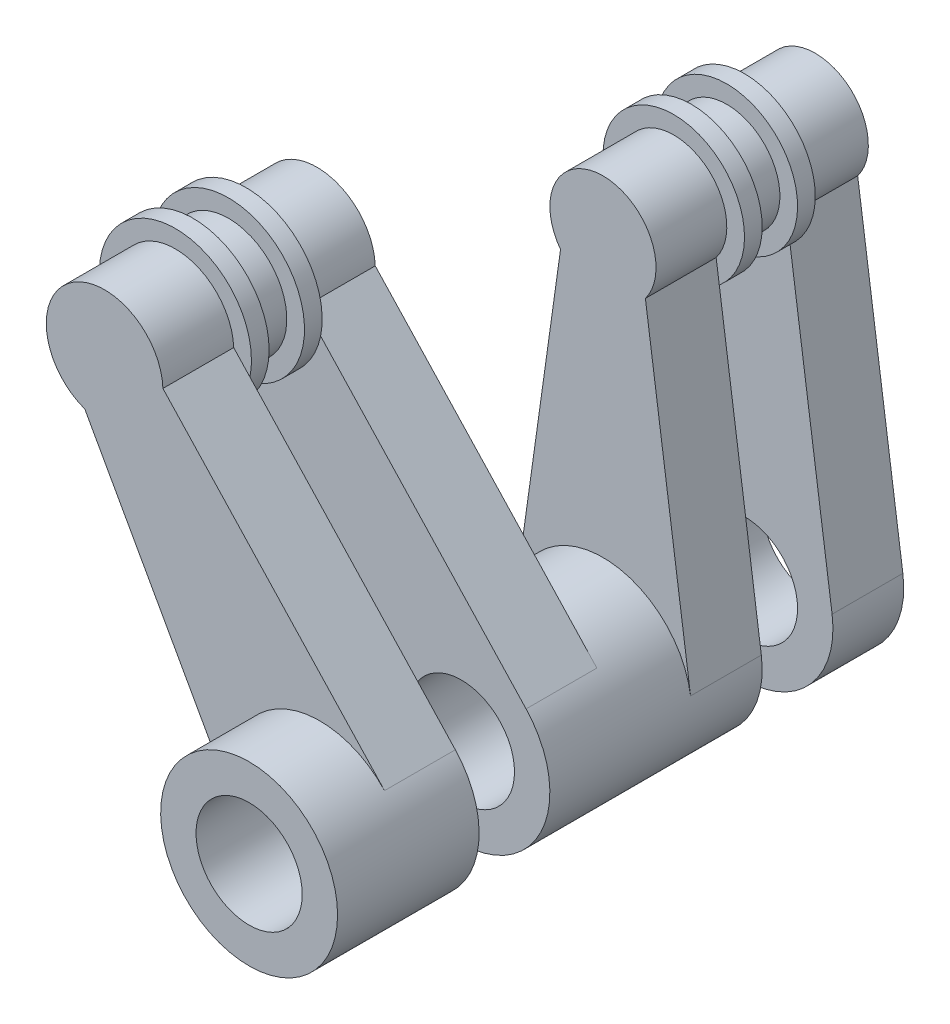
SolidWorks part; units mm, degrees
material "Ferro fundido maleável"
ref_plane "Plano frontal" through (0, 0, 0) normal (0, 0, 1) x (1, 0, 0)
ref_plane "Plano superior" through (0, 0, 0) normal (0, 1, 0) x (1, 0, 0)
ref_plane "Plano direito" through (0, 0, 0) normal (1, 0, 0) x (0, 0, -1)
sketch "Esboço1" plane through (0, 0, 0) normal (0, 0, 1) x (1, 0, 0)
  line L0 (-1.1988, 9.4384) -> (-2.4757, 0.3477)
  line L1 (1.1989, 9.4385) -> (2.4757, 0.3477)
  arc A0 (-2.4757, 0.3477) -> (2.4757, 0.3477) centre (0, 0) ccw
  arc A1 (1.1989, 9.4385) -> (-1.1988, 9.4384) centre (0, 10.34) ccw
  circle A2 centre (0, 0) radius 1.5
  dimension "D1" = 5
  dimension "D2" = 3
  dimension "D4" = 9.1799
  dimension "D3" = 10.34
  dimension "D5" = 9.18
extrude "Ressalto-extrusão1" add sketch "Esboço1" along normal blind 2
sketch "Esboço2" plane through (0, 0, 2) normal (0, 0, 1) x (1, 0, 0)
  circle A0 centre (0, 10.34) radius 1.5
extrude "Ressalto-extrusão2" add sketch "Esboço2" along normal blind 1
mirror "Espelhar1" about plane through (0, 10.34, 3) normal (0, 0, 1) of bodies 128
sketch "Esboço4" plane through (0, 0, 6) normal (0, 0, 1) x (1, 0, 0)
  circle A0 centre (0, 0) radius 2.5
  circle A1 centre (0, 0) radius 1.5
extrude "Ressalto-extrusão3" add sketch "Esboço4" along normal blind 2
sketch "Esboço5" plane through (0, 0, 8) normal (0, 0, 1) x (1, 0, 0)
  line L4 (0, 0) -> (-6.0836, 8.361) construction
  line L5 (0, 0) -> (0, 10.34) construction
  line L6 (-6.6438, 6.8104) -> (-2.1854, -1.2142)
  line L7 (-4.4359, 8.4169) -> (1.8277, 1.7058)
  arc A5 (-2.1854, -1.2142) -> (1.8277, 1.7058) centre (0, 0) ccw
  arc A7 (-4.4359, 8.4169) -> (-6.6438, 6.8104) centre (-6.0836, 8.361) ccw
  circle A9 centre (0, 0) radius 1.5
  dimension "D1" = 10.34
  dimension "D2" = 36.04
  dimension "D3" = 10.34
  dimension "D4" = 5
  dimension "D5" = 3
  dimension "D6" = 3.2972
  dimension "D7" = 9.18
  dimension "D8" = 9.18
extrude "Ressalto-extrusão4" add sketch "Esboço5" along normal blind 2
sketch "Esboço6" plane through (0, 0, 10) normal (0, 0, 1) x (1, 0, 0)
  circle A0 centre (-6.0836, 8.361) radius 1.6486
extrude "Ressalto-extrusão5" add sketch "Esboço6" along normal blind 1
mirror "Espelhar3" about plane through (-6.0836, 8.361, 11) normal (0, 0, 1) of bodies 132
sketch "Esboço7" plane through (0, 0, 22) normal (0, 0, 1) x (1, 0, 0)
  line L1 (-6.2358, 12.3393) -> (5.7031, 12.3393)
  line L2 (-6.2358, 12.3393) -> (-6.2358, -3.3992)
  line L3 (-6.2358, -3.3992) -> (5.7031, -3.3992)
  line L4 (5.7031, 12.3393) -> (5.7031, -3.3992)
extrude "Corte-extrusão1" cut sketch "Esboço7" against normal up to surface (6 mm away) up to face at (0, 6.0315, 16)
sketch "Esboço8" plane through (0, 0, 14) normal (0, 0, 1) x (1, 0, 0)
  circle A2 centre (-6.0836, 8.361) radius 2.1486
extrude "Ressalto-extrusão6" add sketch "Esboço8" against normal blind 0.5 from offset 2 offset against normal yes
sketch "Esboço9" plane through (0, 0, 8) normal (0, 0, -1) x (-1, 0, 0)
  circle A0 centre (6.0836, 8.361) radius 2.1486
extrude "Ressalto-extrusão7" add sketch "Esboço9" along normal blind 0.5 from offset 2.5 offset against normal yes
sketch "Esboço10" plane through (0, 0, 0) normal (0, 0, -1) x (-1, 0, 0)
  circle A0 centre (0, 10.34) radius 2
  arc A1 (1.1988, 9.4384) -> (-1.1989, 9.4385) centre (0, 10.34) ccw construction
  dimension "D1" = 0.5
extrude "Ressalto-extrusão8" add sketch "Esboço10" along normal blind 0.5 from offset 2.5 offset against normal yes
sketch "Esboço11" plane through (0, 0, 6) normal (0, 0, 1) x (1, 0, 0)
  circle A0 centre (0, 10.34) radius 2
extrude "Ressalto-extrusão9" add sketch "Esboço11" along normal blind 0.5 from offset 2.5
